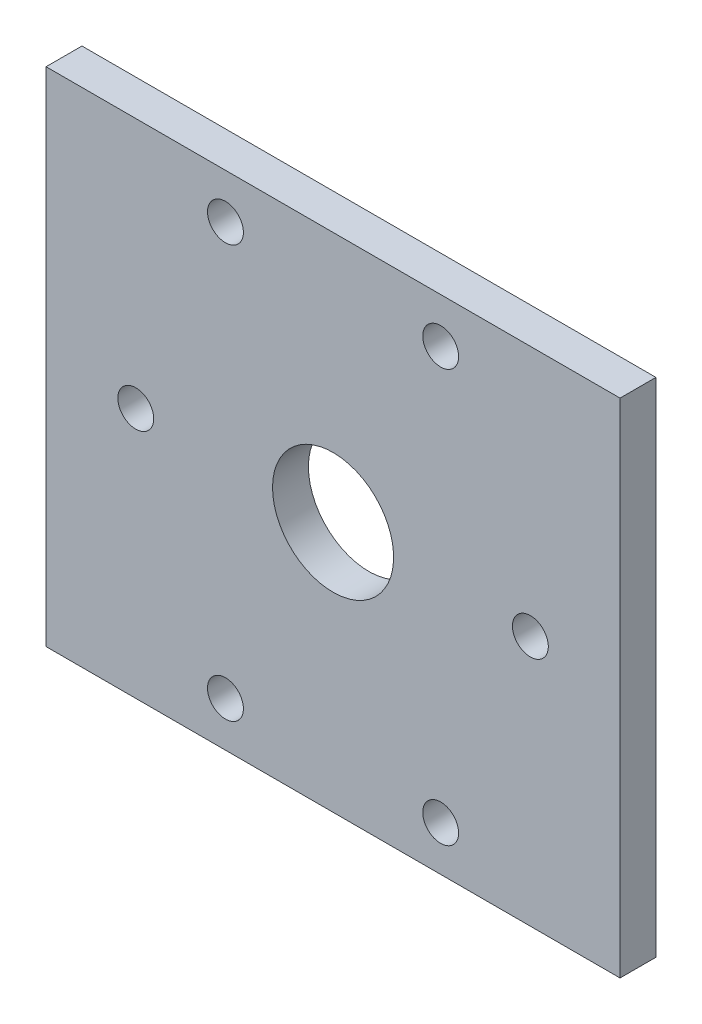
SolidWorks part; units mm, degrees
ref_plane "Front Plane" through (0, 0, 0) normal (0, 0, 1) x (1, 0, 0)
ref_plane "Top Plane" through (0, 0, 0) normal (0, 1, 0) x (1, 0, 0)
ref_plane "Right Plane" through (0, 0, 0) normal (1, 0, 0) x (0, 0, -1)
sketch "Sketch1" plane through (0, 0, 0) normal (0, 0, 1) x (1, 0, 0)
  line L0 (-32, 28) -> (32, 28)
  line L1 (-32, 28) -> (-32, -28)
  line L2 (-32, -28) -> (32, -28)
  line L3 (32, 28) -> (32, -28)
  circle A0 centre (-12, 23) radius 2
  circle A1 centre (12, 23) radius 2
  circle A2 centre (-12, -23) radius 2
  circle A3 centre (12, -23) radius 2
extrude "Boss-Extrude1" add sketch "Sketch1" along normal blind 4
sketch "Sketch2" plane through (0, 0, 0) normal (0, 0, -1) x (-1, 0, 0)
  circle A0 centre (0, 0) radius 6.75
  dimension "D1" = 13.5
extrude "Cut-Extrude1" cut sketch "Sketch2" against normal blind 4
sketch "Sketch3" plane through (0, 0, 0) normal (0, 0, -1) x (-1, 0, 0)
  line L0 (32, 28) -> (32, -28) construction
  line L1 (-32, -28) -> (-32, 28) construction
  circle A0 centre (-22, 0) radius 2
  circle A1 centre (22, 0) radius 2
  dimension "D1" = 10
  dimension "D2" = 10
  dimension "D3" = 4
  dimension "D4" = 4
extrude "Cut-Extrude2" cut sketch "Sketch3" against normal blind 4
